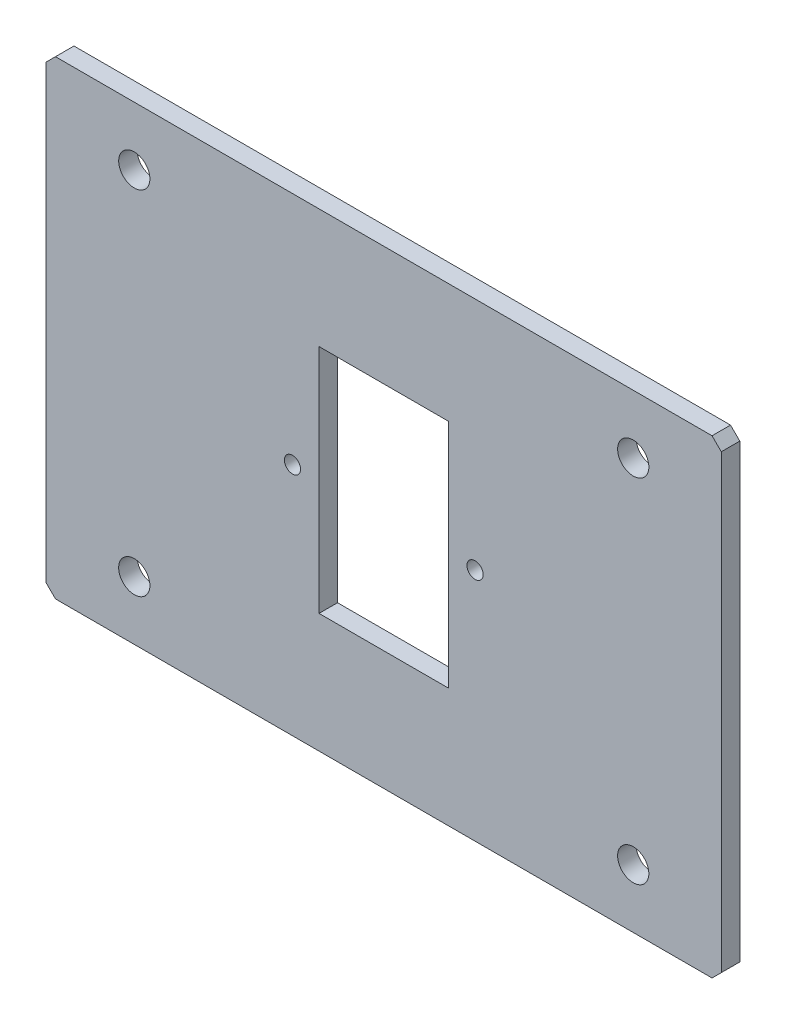
SolidWorks part; units mm, degrees
ref_plane "Front Plane" through (0, 0, 0) normal (0, 0, 1) x (1, 0, 0)
ref_plane "Top Plane" through (0, 0, 0) normal (0, 1, 0) x (1, 0, 0)
ref_plane "Right Plane" through (0, 0, 0) normal (1, 0, 0) x (0, 0, -1)
sketch "Sketch1" plane through (0, 0, 0) normal (0, 0, 1) x (1, 0, 0)
  line L0 (-19.75, 0) -> (19.75, 0)
  line L1 (-73.025, -50.8) -> (73.025, -50.8)
  line L2 (-73.025, -50.8) -> (-73.025, 50.8)
  line L3 (-73.025, 50.8) -> (73.025, 50.8)
  line L4 (73.025, -50.8) -> (73.025, 50.8)
  line L5 (-73.025, -50.8) -> (73.025, 50.8) construction
  line L6 (-73.025, 50.8) -> (73.025, -50.8) construction
  line L7 (-47.625, -25.4) -> (47.625, -25.4) construction
  line L8 (-47.625, -25.4) -> (-47.625, 25.4) construction
  line L9 (-47.625, 25.4) -> (47.625, 25.4) construction
  line L10 (47.625, -25.4) -> (47.625, 25.4) construction
  line L11 (-47.625, -25.4) -> (47.625, 25.4) construction
  line L12 (-47.625, 25.4) -> (47.625, -25.4) construction
  line L13 (-14, -25) -> (14, -25)
  line L14 (-14, -25) -> (-14, 25)
  line L15 (-14, 25) -> (14, 25)
  line L16 (14, -25) -> (14, 25)
  line L17 (-14, -25) -> (14, 25) construction
  line L18 (-14, 25) -> (14, -25) construction
  circle A0 centre (-19.75, 0) radius 1.75
  circle A1 centre (19.75, 0) radius 1.75
  point P0 (0, 0)
  point P6 (0, 0)
  point P11 (0, 0)
  point P19 (0, 0)
  dimension "D8" = 3.5
  dimension "D1" = 101.6
  dimension "D2" = 146.05
  dimension "D3" = 95.25
  dimension "D4" = 50.8
  dimension "D5" = 28
  dimension "D6" = 50
  dimension "D7" = 39.5
extrude "Boss-Extrude1" add sketch "Sketch1" along normal blind 4
hole_wizard "1/4 Clearance Hole1" positions "Sketch2" profile "Sketch3" hole size "1/4" standard "ANSI Inch"
sketch "Sketch2" plane through (0, 0, 4) normal (0, 0, 1) x (1, 0, 0)
  line L0 (-73.025, 50.8) -> (73.025, 50.8) construction
  line L1 (73.025, -50.8) -> (73.025, 50.8) construction
  line L2 (-73.025, -50.8) -> (-73.025, 50.8) construction
  line L3 (-73.025, -50.8) -> (73.025, -50.8) construction
  point P0 (-53.975, 38.1)
  point P2 (53.975, 38.1)
  point P4 (53.975, -38.1)
  point P6 (-53.975, -38.1)
  point P9 (0, 0)
  point P10 (0, 0)
  point P11 (0, 0)
  point P12 (0, 0)
  dimension "D1" = 12.7
  dimension "D2" = 19.05
  dimension "D3" = 19.05
  dimension "D4" = 12.7
sketch "Sketch3" plane through (-53.975, 38.1, 4) normal (1, 0, 0) x (0, -1, 0)
  line L0 (0, 0) -> (0, 14.0298)
  line L1 (0, 14.0298) -> (3.3782, 12)
  line L2 (3.3782, 12) -> (3.3782, 0)
  line L5 (3.3782, 0) -> (0, 0)
  line L10 (0, 14.0298) -> (-3.3782, 12) construction
  line L11 (0, -6.35) -> (0, 107.95) construction
  dimension "Hole Dia." = 6.7564
  dimension "Hole Depth" = 12
  dimension "Drill Angle" = 118
chamfer "Chamfer1" distance 2 angle 45 4 edges at (73.025, 50.8, 2) (73.025, -50.8, 2) (-73.025, -50.8, 2) (-73.025, 50.8, 2)
